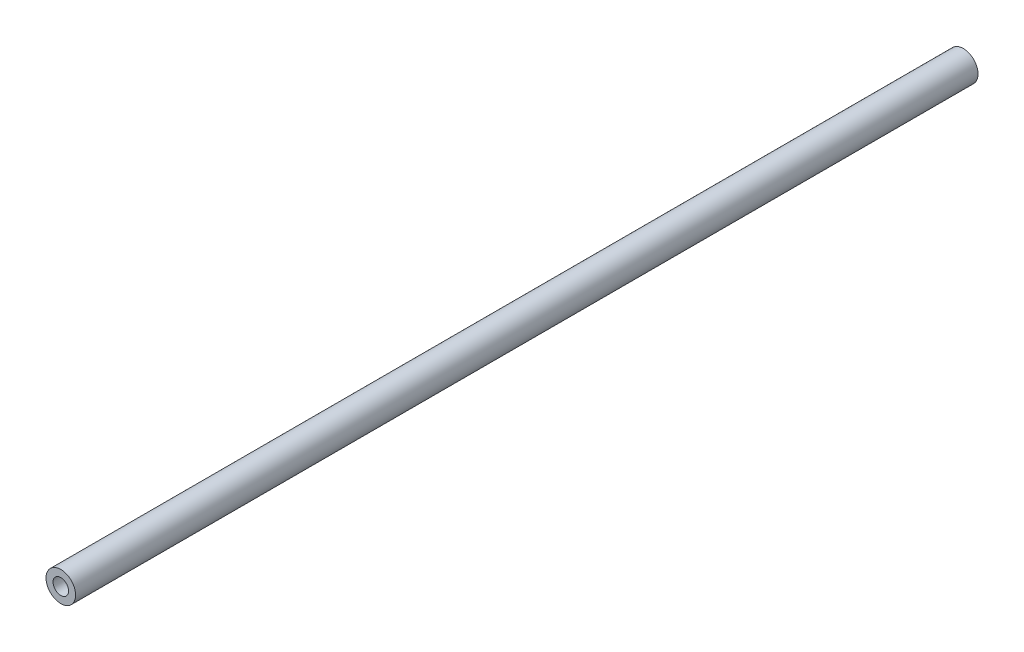
SolidWorks part; units mm, degrees
ref_plane "前视基准面" through (0, 0, 0) normal (0, 0, 1) x (1, 0, 0)
ref_plane "上视基准面" through (0, 0, 0) normal (0, 1, 0) x (1, 0, 0)
ref_plane "右视基准面" through (0, 0, 0) normal (1, 0, 0) x (0, 0, -1)
sketch "草图1" plane through (0, 0, 0) normal (0, 0, 1) x (1, 0, 0)
  circle A0 centre (0, 0) radius 4
extrude "凸台-拉伸1" add sketch "草图1" along normal mid plane 243.9
hole_wizard "M5 螺纹孔的螺纹孔钻头1" positions "3D草图1" profile "草图3" hole size "M5" standard "GB" end condition through all
sketch3d "3D草图1"
  line L0 (0, 0, 121.95) -> (0, 0, -121.95) construction
  point P0 (0, 0, 0)
  point P3 (0, 0, 121.95)
sketch "草图3" plane through (0, 0, 121.95) normal (1, 0, 0) x (0, -1, 0)
  line L0 (0, 0) -> (0, 243.9)
  line L1 (0, 243.9) -> (2.1, 243.9)
  line L2 (2.1, 243.9) -> (2.1, 0)
  line L5 (2.1, 0) -> (0, 0)
  line L11 (0, -6.35) -> (0, 107.95) construction
  dimension "通孔孔直径" = 4.2
  dimension "通孔孔深度" = 243.9
